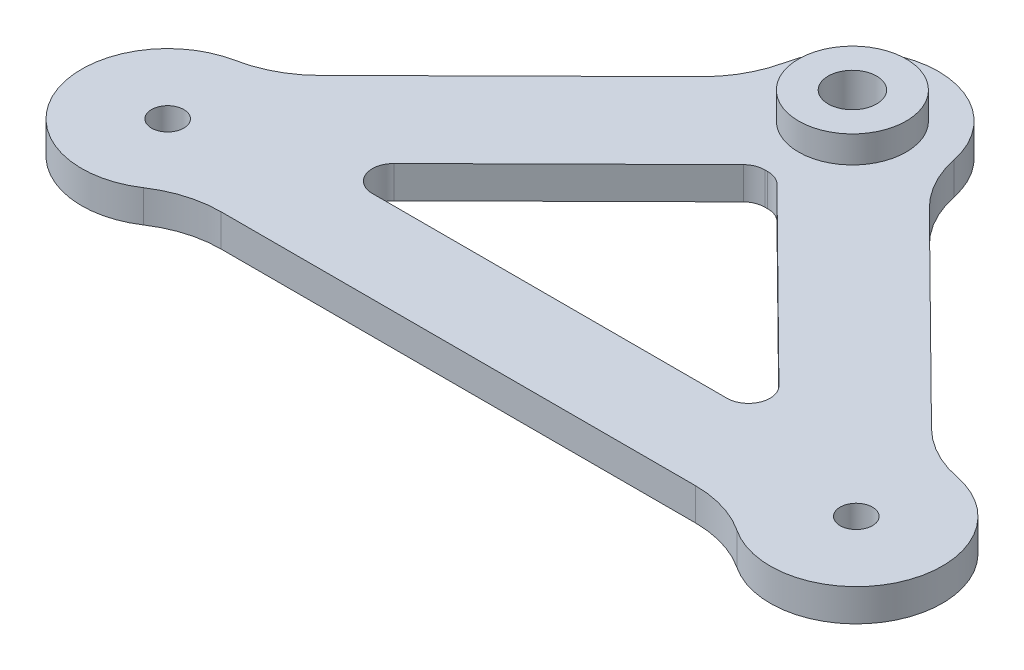
SolidWorks part; units mm, degrees
ref_plane "Front Plane" through (0, 0, 0) normal (0, 0, 1) x (1, 0, 0)
ref_plane "Top Plane" through (0, 0, 0) normal (0, 1, 0) x (1, 0, 0)
ref_plane "Right Plane" through (0, 0, 0) normal (1, 0, 0) x (0, 0, -1)
sketch "Sketch2" plane through (0, 0, 0) normal (0, 1, 0) x (1, 0, 0)
  line L0 (0, 34.3023) -> (0, -20.3488) construction
  line L1 (-35.5154, 1.464) -> (-3.5154, 33.1026)
  line L2 (-28.4846, -5.6471) -> (-0.9255, 21.6008)
  line L3 (-32, -7.0915) -> (32, -7.0915)
  line L4 (32, 2.9085) -> (-32, 2.9085)
  line L5 (35.446, 1.5314) -> (3.5155, 33.1025)
  line L6 (-3.446, 25.9242) -> (0.0006, 22.5164)
  line L7 (0, 22.5158) -> (3.5154, 25.9915)
  line L8 (0.9265, 21.6009) -> (29.3058, -6.459)
  line L9 (-28.4293, 1.4085) -> (28.4293, 1.4085)
  circle A0 centre (-32, -2.0915) radius 5
  circle A1 centre (32, -2.0915) radius 5
  circle A2 centre (0, 29.5471) radius 5
  circle A3 centre (-32, -2.0915) radius 8
  circle A4 centre (0, 29.5471) radius 8
  circle A5 centre (32, -2.0915) radius 8
  circle A6 centre (-32, -2.0915) radius 1.5
  circle A7 centre (32, -2.0915) radius 1.5
  dimension "D3" = 10
  dimension "D4" = 10
  dimension "D5" = 10
  dimension "D6" = 16
  dimension "D7" = 16
  dimension "D8" = 16
  dimension "D9" = 64
  dimension "D11" = 3
  dimension "D12" = 3
  dimension "D1" = 45
  dimension "D2" = 45
  dimension "D10" = 31.6386
  dimension "D13" = 1.5
extrude "Boss-Extrude1" add sketch "Sketch2" along normal blind 3
fillet "Fillet1" radius 10 6 edges at (7.9563, 1.5, -28.7117) (31.0735, 1.5, -5.8546) (25.755, 1.5, 7.0915) (-25.755, 1.5, 7.0915) (-31.0745, 1.5, -5.8548) (-7.9563, 1.5, -28.7119)
fillet "Fillet2" radius 2 4 edges at (0.9265, 1.5, -21.6009) (-0.9255, 1.5, -21.6008) (21.3487, 1.5, -1.4085) (-21.3484, 1.5, -1.4085)
sketch "Sketch3" plane through (0, 3, 0) normal (0, 1, 0) x (1, 0, 0)
  circle A0 centre (0, 29.5471) radius 5
  circle A1 centre (0, 29.5471) radius 2.25
  dimension "D1" = 4.5
extrude "Boss-Extrude2" add sketch "Sketch3" against normal blind 3 and the other way blind 2.5 separate body
